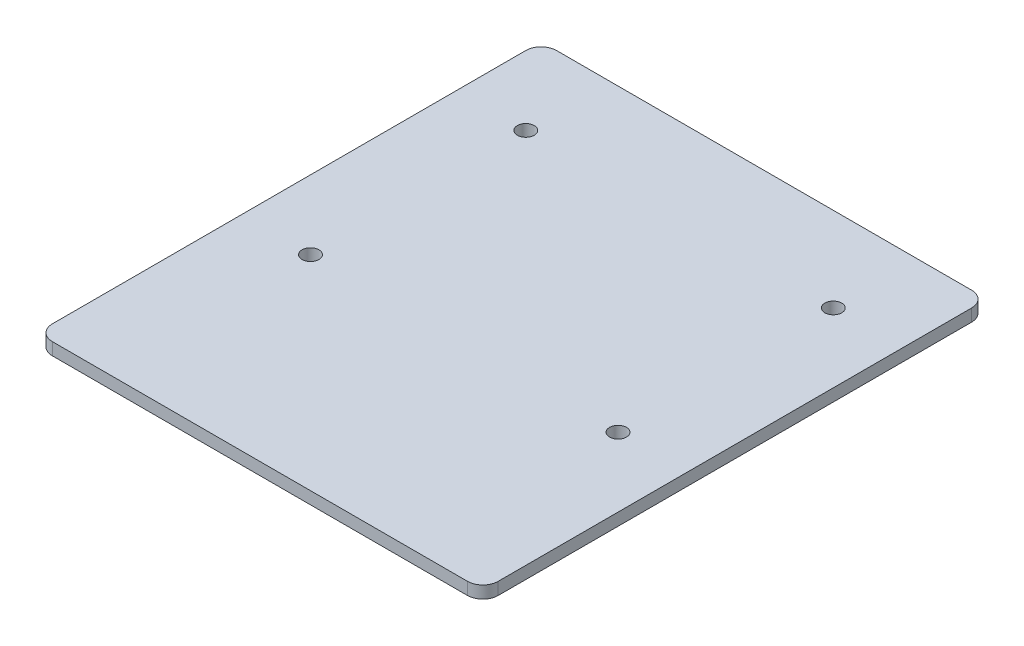
SolidWorks part; units mm, degrees
ref_plane "前视基准面" through (0, 0, 0) normal (0, 0, 1) x (1, 0, 0)
ref_plane "上视基准面" through (0, 0, 0) normal (0, 1, 0) x (1, 0, 0)
ref_plane "右视基准面" through (0, 0, 0) normal (1, 0, 0) x (0, 0, -1)
other "Configuration Table"
sketch "草图1" plane through (0, 0, 0) normal (0, 1, 0) x (1, 0, 0)
  line L1 (-72.5, 19.5) -> (72.5, 19.5)
  line L2 (-72.5, 19.5) -> (-72.5, -144.4657)
  line L3 (-72.5, -144.4657) -> (72.5, -144.4657)
  line L4 (72.5, 19.5) -> (72.5, -144.4657)
extrude "承托板_145x120x4mm" add sketch "草图1" along normal blind 4
sketch "草图2" plane through (0, 4, 0) normal (0, 1, 0) x (1, 0, 0)
  circle A0 centre (-50, -8) radius 2.75
  circle A1 centre (-50, -78) radius 2.75
  circle A2 centre (50, -8) radius 2.75
  circle A3 centre (50, -78) radius 2.75
  dimension "D1" = 50
  dimension "D2" = 50
  dimension "D3" = 50
  dimension "D4" = 50
  dimension "D5" = 5.5
  dimension "D6" = 5.5
  dimension "D7" = 5.5
  dimension "D8" = 5.5
  dimension "D9" = 70
extrude "四个M3连接孔_90x70mm" cut sketch "草图2" against normal through all
fillet "四角圆角_R5" radius 5 4 edges at (-72.5, 2, -19.5) (72.5, 2, -19.5) (72.5, 2, 144.4657) (-72.5, 2, 144.4657)
